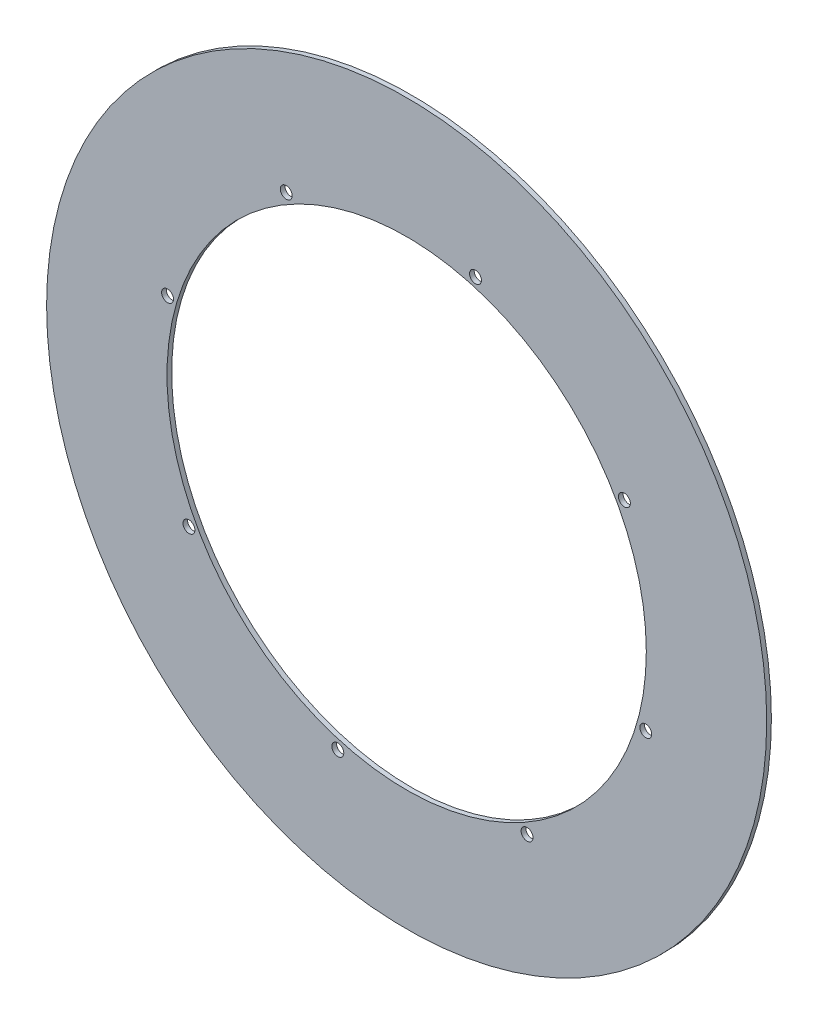
SolidWorks part; units mm, degrees
ref_plane "Front Plane" through (0, 0, 0) normal (0, 0, 1) x (1, 0, 0)
ref_plane "Top Plane" through (0, 0, 0) normal (0, 1, 0) x (1, 0, 0)
ref_plane "Right Plane" through (0, 0, 0) normal (1, 0, 0) x (0, 0, -1)
sketch "Sketch1" plane through (0, 0, 0) normal (0, 0, 1) x (1, 0, 0)
  circle A0 centre (0, 0) radius 102.5 construction
  circle A1 centre (0, 0) radius 102.5
  circle A3 centre (0, 0) radius 154
  circle A4 centre (102.2639, -29.4395) radius 2.5447 construction
  circle A5 centre (93.1284, 51.4946) radius 2.5447 construction
  circle A6 centre (51.4946, -93.1284) radius 2.5447 construction
  circle A7 centre (-29.4395, -102.2639) radius 2.5447 construction
  circle A8 centre (-93.1284, -51.4946) radius 2.5447 construction
  circle A9 centre (-102.2639, 29.4395) radius 2.5447 construction
  circle A10 centre (-51.4946, 93.1284) radius 2.5447 construction
  circle A11 centre (29.4395, 102.2639) radius 2.5447 construction
  circle A12 centre (102.2639, -29.4395) radius 2.5447
  circle A13 centre (93.1284, 51.4946) radius 2.5447
  circle A14 centre (51.4946, -93.1284) radius 2.5447
  circle A15 centre (-29.4395, -102.2639) radius 2.5447
  circle A16 centre (-93.1284, -51.4946) radius 2.5447
  circle A17 centre (-102.2639, 29.4395) radius 2.5447
  circle A18 centre (-51.4946, 93.1284) radius 2.5447
  circle A19 centre (29.4395, 102.2639) radius 2.5447
  dimension "D1" = 308
extrude "Boss-Extrude1" add sketch "Sketch1" along normal blind 2
